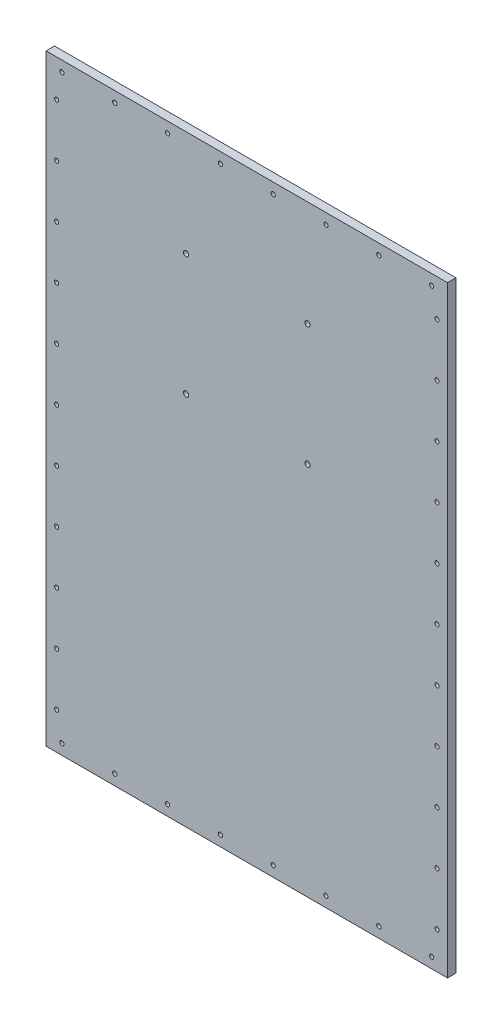
SolidWorks part; units mm, degrees
ref_plane "前视基准面" through (0, 0, 0) normal (0, 0, 1) x (1, 0, 0)
ref_plane "上视基准面" through (0, 0, 0) normal (0, 1, 0) x (1, 0, 0)
ref_plane "右视基准面" through (0, 0, 0) normal (1, 0, 0) x (0, 0, -1)
sketch "草图1" plane through (0, 0, 0) normal (0, 0, 1) x (1, 0, 0)
  line L1 (-190, 285) -> (190, 285)
  line L2 (-190, 285) -> (-190, -285)
  line L3 (-190, -285) -> (190, -285)
  line L4 (190, 285) -> (190, -285)
  line L5 (-190, 285) -> (190, -285) construction
  line L6 (-190, -285) -> (190, 285) construction
  point P0 (0, 0)
  dimension "D1" = 380
  dimension "D2" = 570
extrude "凸台-拉伸1" add sketch "草图1" along normal blind 8
sketch "草图2" plane through (0, 0, 8) normal (0, 0, 1) x (1, 0, 0)
  line L0 (-180, 285) -> (-180, -285) construction
  line L1 (190, 285) -> (-190, 285) construction
  line L2 (-190, -285) -> (190, -285) construction
  line L3 (-190, 285) -> (-190, -285) construction
  line L4 (0, 285) -> (0, -285) construction
  line L5 (180, 285) -> (180, -285) construction
  circle A0 centre (-180, 250) radius 2
  circle A1 centre (-180, 200) radius 2
  circle A2 centre (-180, 150) radius 2
  circle A3 centre (-180, 100) radius 2
  circle A4 centre (-180, 50) radius 2
  circle A5 centre (-180, 0) radius 2
  circle A6 centre (-180, -50) radius 2
  circle A7 centre (-180, -100) radius 2
  circle A8 centre (-180, -150) radius 2
  circle A9 centre (-180, -200) radius 2
  circle A10 centre (-180, -250) radius 2
  circle A11 centre (180, -250) radius 2
  circle A12 centre (180, -200) radius 2
  circle A13 centre (180, -150) radius 2
  circle A14 centre (180, -100) radius 2
  circle A15 centre (180, -50) radius 2
  circle A16 centre (180, 0) radius 2
  circle A17 centre (180, 50) radius 2
  circle A18 centre (180, 100) radius 2
  circle A19 centre (180, 150) radius 2
  circle A20 centre (180, 200) radius 2
  circle A21 centre (180, 250) radius 2
  dimension "D2" = 4
  dimension "D1" = 10
  dimension "D3" = 35
  dimension "D4" = 11
extrude "切除-拉伸1" cut sketch "草图2" against normal up to next
sketch "草图3" plane through (0, 0, 8) normal (0, 0, 1) x (1, 0, 0)
  line L0 (-190, -285) -> (190, -285) construction
  line L1 (-57.5, 185) -> (57.5, 185)
  line L2 (-57.5, 185) -> (-57.5, 70)
  line L3 (-57.5, 70) -> (57.5, 70)
  line L4 (57.5, 185) -> (57.5, 70)
  line L5 (-57.5, 185) -> (57.5, 70) construction
  line L6 (-57.5, 70) -> (57.5, 185) construction
  line L7 (0, 285) -> (0, -285) construction
  line L8 (190, 285) -> (-190, 285) construction
  circle A0 centre (-57.5, 185) radius 2.5
  circle A1 centre (57.5, 185) radius 2.5
  circle A2 centre (57.5, 70) radius 2.5
  circle A3 centre (-57.5, 70) radius 2.5
  point P0 (0, 127.5)
  dimension "D4" = 5
  dimension "D1" = 115
  dimension "D2" = 115
  dimension "D3" = 355
extrude "切除-拉伸2" cut sketch "草图3" against normal up to next contours A0 | A1 | A2 | A3
sketch "草图4" plane through (0, 0, 8) normal (0, 0, 1) x (1, 0, 0)
  line L0 (-190, 275) -> (190, 275) construction
  line L1 (-190, 285) -> (-190, -285) construction
  line L2 (190, -285) -> (190, 285) construction
  line L3 (190, 285) -> (-190, 285) construction
  line L4 (-190, 0) -> (190, 0) construction
  line L5 (-190, -275) -> (190, -275) construction
  circle A0 centre (-175, 275) radius 2
  circle A1 centre (-125, 275) radius 2
  circle A2 centre (-75, 275) radius 2
  circle A3 centre (-25, 275) radius 2
  circle A4 centre (25, 275) radius 2
  circle A5 centre (75, 275) radius 2
  circle A6 centre (125, 275) radius 2
  circle A7 centre (175, 275) radius 2
  circle A8 centre (175, -275) radius 2
  circle A9 centre (125, -275) radius 2
  circle A10 centre (75, -275) radius 2
  circle A11 centre (25, -275) radius 2
  circle A12 centre (-25, -275) radius 2
  circle A13 centre (-75, -275) radius 2
  circle A14 centre (-125, -275) radius 2
  circle A15 centre (-175, -275) radius 2
  dimension "D2" = 4
  dimension "D1" = 10
  dimension "D3" = 15
  dimension "D4" = 8
extrude "切除-拉伸3" cut sketch "草图4" against normal up to next
